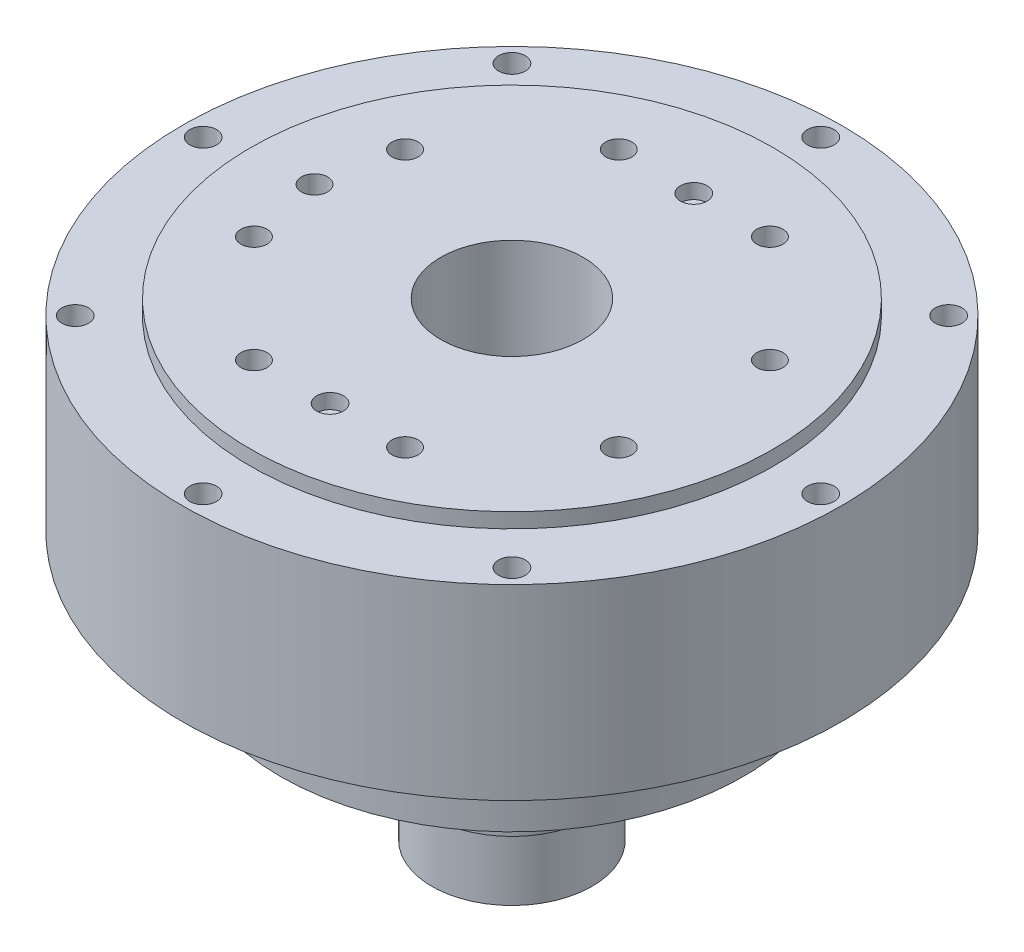
SolidWorks part; units mm, degrees
ref_plane "Front Plane" through (0, 0, 0) normal (0, 0, 1) x (1, 0, 0)
ref_plane "Top Plane" through (0, 0, 0) normal (0, 1, 0) x (1, 0, 0)
ref_plane "Right Plane" through (0, 0, 0) normal (1, 0, 0) x (0, 0, -1)
sketch "Sketch1" plane through (0, 0, 0) normal (1, 0, 0) x (0, 0, -1)
  line L0 (0, 0) -> (-27, 0)
  line L1 (-27, 0) -> (-27, 20.5)
  line L2 (-27, 20.5) -> (-27.5, 20.5)
  line L3 (-27.5, 20.5) -> (-27.5, 45.55)
  line L4 (-27.5, 45.55) -> (-42.5, 45.55)
  line L5 (-42.5, 45.55) -> (-42.5, 57.55)
  line L8 (-42.5, 57.55) -> (-78, 57.55)
  line L9 (-78, 57.55) -> (-78, 67.843)
  line L10 (-78, 67.843) -> (-42.9119, 67.843)
  line L11 (-42.9119, 67.843) -> (-42.9119, 74.5688)
  line L12 (-42.9119, 74.5688) -> (-50.1462, 74.5688)
  line L13 (-50.1462, 74.5688) -> (-50.1462, 79)
  line L14 (-50.1462, 79) -> (-85.75, 79)
  line L15 (-85.75, 79) -> (-85.75, 90)
  line L20 (-85.75, 90) -> (-111, 90)
  line L23 (-111, 90) -> (-111, 153)
  line L24 (-111, 153) -> (-88, 153)
  line L25 (-88, 153) -> (-88, 158)
  line L26 (-88, 158) -> (0, 158)
  line L27 (0, 158) -> (0, 0)
  line L28 (0, 0) -> (0, 248.8585) construction
  dimension "D1" = 54
  dimension "D2" = 55
  dimension "D3" = 85
  dimension "D4" = 156
  dimension "D5" = 171.5
  dimension "D8" = 222
  dimension "D10" = 176
  dimension "D11" = 20.5
  dimension "D12" = 5
  dimension "D13" = 63
  dimension "D14" = 11
  dimension "D15" = 32.45
  dimension "D16" = 44.45
  dimension "D17" = 79
revolve "Revolve1" add sketch "Sketch1" angle 360 about L28
sketch "Sketch2" plane through (0, 153, 0) normal (0, 1, 0) x (1, 0, 0)
  line L0 (0, 0) -> (-178.8301, 0) construction
  circle A0 centre (0, 0) radius 104 construction
  circle A1 centre (-104, 0) radius 4.5
  circle A9 centre (-73.5391, 73.5391) radius 4.5
  circle A10 centre (0, 104) radius 4.5
  circle A11 centre (73.5391, 73.5391) radius 4.5
  circle A12 centre (104, 0) radius 4.5
  circle A13 centre (73.5391, -73.5391) radius 4.5
  circle A14 centre (0, -104) radius 4.5
  circle A15 centre (-73.5391, -73.5391) radius 4.5
  point P23 (0, 0)
  dimension "D1" = 9
  dimension "D4" = 208
  dimension "D2" = 8
extrude "Cut-Extrude1" cut sketch "Sketch2" against normal through all
sketch "Sketch4" plane through (0, 158, 0) normal (0, 1, 0) x (1, 0, 0)
  line L0 (0, 0) -> (-172.1172, 0) construction
  line L1 (0, 0) -> (-66.5, 0) construction
  line L2 (0, 0) -> (-61.438, 25.4484) construction
  circle A0 centre (0, 0) radius 66.5 construction
  circle A1 centre (-66.5, 0) radius 4.4
  circle A2 centre (-61.438, 25.4484) radius 4.4
  circle A4 centre (-25.4484, 61.438) radius 4.4
  circle A6 centre (25.4484, 61.438) radius 4.4
  circle A8 centre (61.438, 25.4484) radius 4.4
  circle A10 centre (61.438, -25.4484) radius 4.4
  circle A12 centre (25.4484, -61.438) radius 4.4
  circle A14 centre (-25.4484, -61.438) radius 4.4
  circle A16 centre (-61.438, -25.4484) radius 4.4
  circle A17 centre (-47.0226, 47.0226) radius 4.4 [skipped]
  circle A18 centre (-47.0226, -47.0226) radius 4.4 [skipped]
  circle A19 centre (0, -66.5) radius 4.4 [skipped]
  circle A20 centre (47.0226, -47.0226) radius 4.4 [skipped]
  circle A21 centre (66.5, 0) radius 4.4 [skipped]
  circle A22 centre (47.0226, 47.0226) radius 4.4 [skipped]
  circle A23 centre (0, 66.5) radius 4.4 [skipped]
  dimension "D1" = 133
  dimension "D2" = 8.8
  dimension "D3" = 16
  dimension "D4" = 22.5
extrude "Cut-Extrude3" cut sketch "Sketch4" against normal blind 18
sketch "Sketch5" plane through (0, 158, 0) normal (0, 1, 0) x (1, 0, 0)
  line L0 (0, 0) -> (0, -129.3283) construction
  circle A0 centre (0, 0) radius 61.25 construction
  circle A1 centre (0, -61.25) radius 4.5
  circle A3 centre (0, 61.25) radius 4.5
  circle A5 centre (-61.25, 0) radius 4.5 [skipped]
  circle A6 centre (61.25, 0) radius 4.5 [skipped]
  point P15 (0, 0)
  dimension "D1" = 122.5
  dimension "D2" = 9
  dimension "D3" = 4
extrude "Cut-Extrude4" cut sketch "Sketch5" against normal blind 5
sketch "Sketch6" plane through (0, 0, 0) normal (0, -1, 0) x (1, 0, 0)
  circle A0 centre (0, 0) radius 24
  dimension "D1" = 48
extrude "Cut-Extrude5" cut sketch "Sketch6" against normal through all
